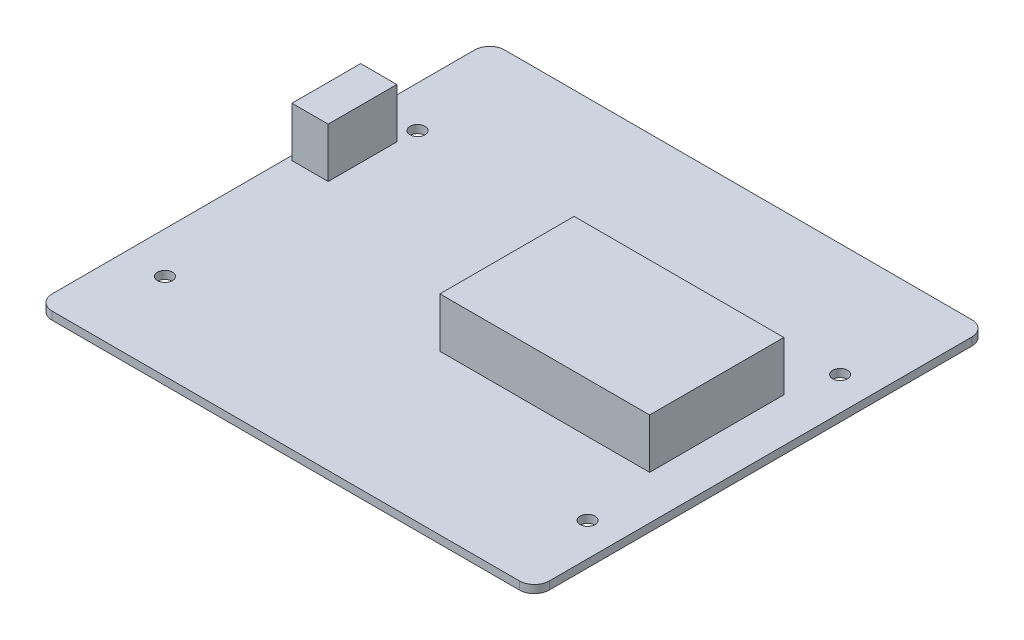
SolidWorks part; units mm, degrees
ref_plane "前视基准面" through (0, 0, 0) normal (0, 0, 1) x (1, 0, 0)
ref_plane "上视基准面" through (0, 0, 0) normal (0, 1, 0) x (1, 0, 0)
ref_plane "右视基准面" through (0, 0, 0) normal (1, 0, 0) x (0, 0, -1)
sketch "草图1" plane through (0, 0, 0) normal (0, 1, 0) x (1, 0, 0)
  line L1 (-47, 45.5) -> (47, 45.5)
  line L2 (-50, 42.5) -> (-50, -42.5)
  line L3 (-47, -45.5) -> (47, -45.5)
  line L4 (50, 42.5) -> (50, -42.5)
  line L5 (-50, 45.5) -> (50, -45.5) construction
  line L6 (-50, -45.5) -> (50, 45.5) construction
  line L7 (-41.7, 22.7) -> (43.3, 22.7) construction
  line L8 (-41.7, 22.7) -> (-41.7, -28.1) construction
  line L9 (-41.7, -28.1) -> (43.3, -28.1) construction
  line L10 (43.3, 22.7) -> (43.3, -28.1) construction
  line L11 (-41.7, 22.7) -> (43.3, -28.1) construction
  line L12 (-41.7, -28.1) -> (43.3, 22.7) construction
  arc A0 (47, -45.5) -> (50, -42.5) centre (47, -42.5) ccw
  arc A1 (-50, -42.5) -> (-47, -45.5) centre (-47, -42.5) ccw
  arc A2 (47, 45.5) -> (50, 42.5) centre (47, 42.5) cw
  arc A3 (-47, 45.5) -> (-50, 42.5) centre (-47, 42.5) ccw
  circle A4 centre (-41.7, 22.7) radius 1.5
  circle A5 centre (43.3, 22.7) radius 1.5
  circle A6 centre (43.3, -28.1) radius 1.5
  circle A7 centre (-41.7, -28.1) radius 1.5
  point P0 (0, 0)
  point P6 (0, 0)
  dimension "D5" = 3
  dimension "D6" = 3
  dimension "D1" = 100
  dimension "D2" = 91
  dimension "D3" = 85
  dimension "D4" = 50.8
  dimension "D7" = 6.7
  dimension "D8" = 22.8
extrude "凸台-拉伸1" add sketch "草图1" along normal blind 1.6
sketch "草图2" plane through (0, 1.6, 0) normal (0, 1, 0) x (1, 0, 0)
  line L1 (-1.0044, 13.4972) -> (41.1821, 13.4972)
  line L2 (-1.0044, 13.4972) -> (-1.0044, -13.4972)
  line L3 (-1.0044, -13.4972) -> (41.1821, -13.4972)
  line L4 (41.1821, 13.4972) -> (41.1821, -13.4972)
  line L5 (-1.0044, 13.4972) -> (41.1821, -13.4972) construction
  line L6 (-1.0044, -13.4972) -> (41.1821, 13.4972) construction
  line L7 (-49.0921, 18.6449) -> (-41.8099, 18.6449)
  line L8 (-49.0921, 18.6449) -> (-49.0921, 4.8339)
  line L9 (-49.0921, 4.8339) -> (-41.8099, 4.8339)
  line L10 (-41.8099, 18.6449) -> (-41.8099, 4.8339)
  line L11 (-49.0921, 18.6449) -> (-41.8099, 4.8339) construction
  line L12 (-49.0921, 4.8339) -> (-41.8099, 18.6449) construction
  point P0 (20.0888, 0)
  point P5 (-45.451, 11.7394)
extrude "凸台-拉伸2" add sketch "草图2" along normal blind 10
